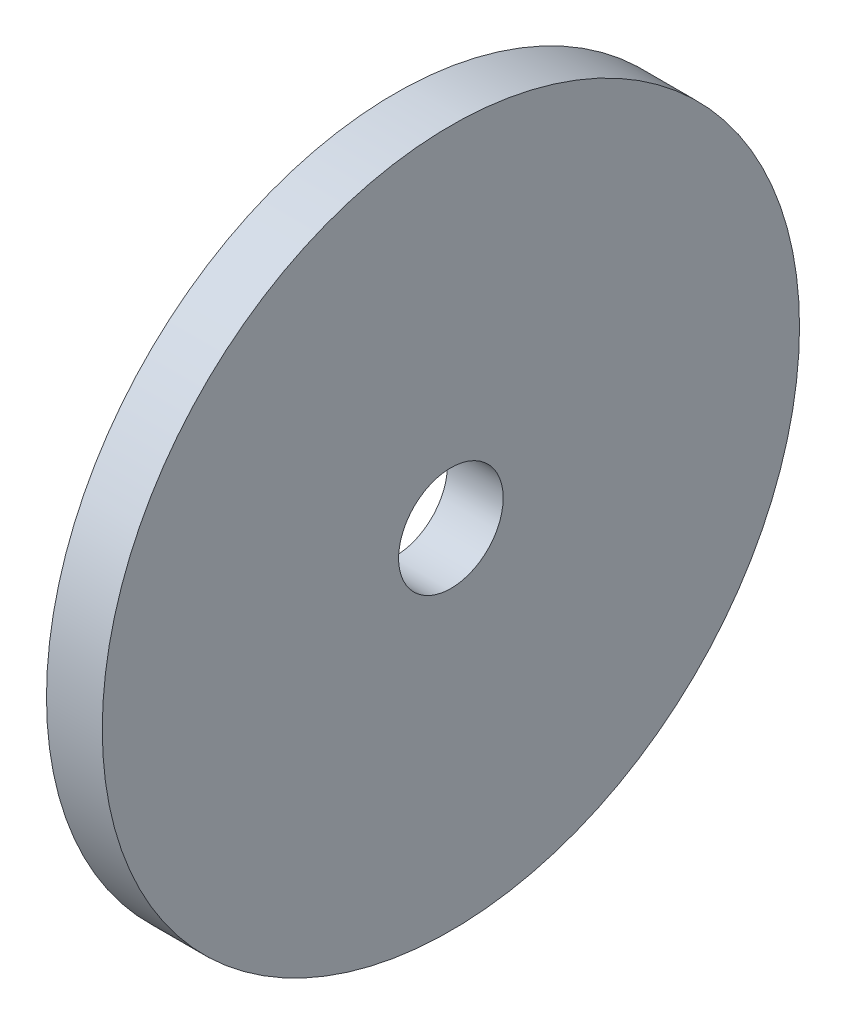
SolidWorks part; units mm, degrees
ref_plane "Front Plane" through (0, 0, 0) normal (0, 0, 1) x (1, 0, 0)
ref_plane "Top Plane" through (0, 0, 0) normal (0, 1, 0) x (1, 0, 0)
ref_plane "Right Plane" through (0, 0, 0) normal (1, 0, 0) x (0, 0, -1)
sketch "Sketch1" plane through (0, 0, 0) normal (1, 0, 0) x (0, 0, -1)
  circle A0 centre (0, 0) radius 17.5
  circle A1 centre (0, 0) radius 2.625
  dimension "D1" = 35
  dimension "D2" = 5.25
extrude "Boss-Extrude1" add sketch "Sketch1" along normal blind 2.8
